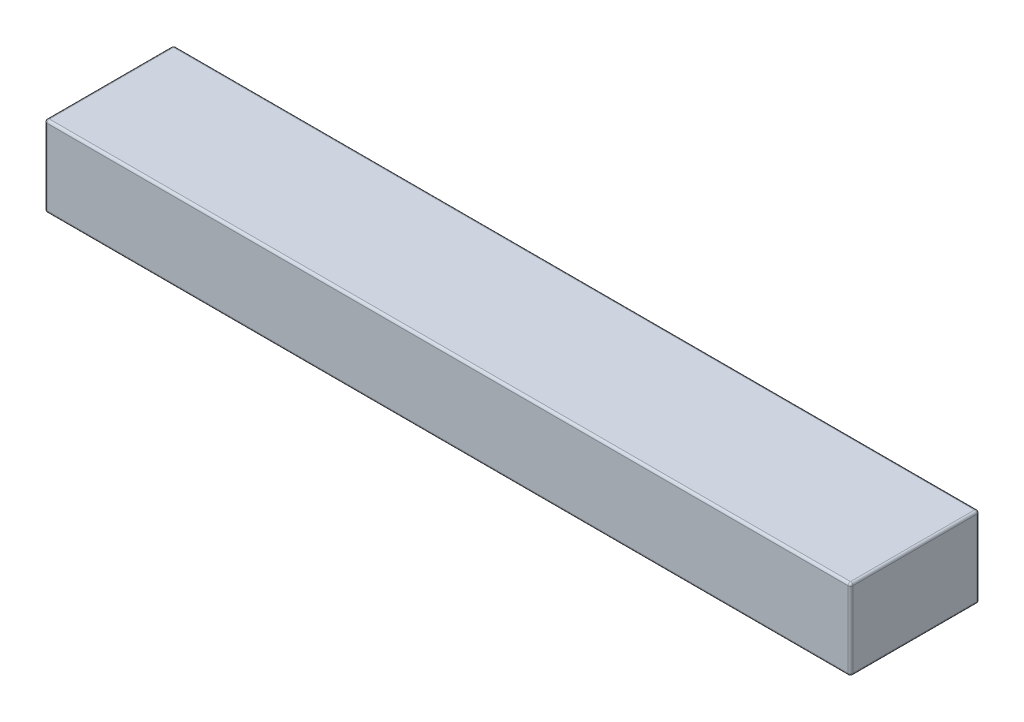
SolidWorks part; units mm, degrees
ref_plane "Front Plane" through (0, 0, 0) normal (0, 0, 1) x (1, 0, 0)
ref_plane "Top Plane" through (0, 0, 0) normal (0, 1, 0) x (1, 0, 0)
ref_plane "Right Plane" through (0, 0, 0) normal (1, 0, 0) x (0, 0, -1)
sketch "Sketch1" plane through (0, 0, 0) normal (1, 0, 0) x (0, 0, -1)
  line L1 (-7.7, -5.7) -> (7.7, -5.7)
  line L2 (-8, -5.4) -> (-8, 4)
  line L3 (-7.7, 4.3) -> (7.7, 4.3)
  line L4 (8, -5.4) -> (8, 4)
  line L5 (-8, -5.7) -> (8, 4.3) construction
  line L6 (-8, 4.3) -> (8, -5.7) construction
  arc A0 (-7.7, -5.7) -> (-8, -5.4) centre (-7.7, -5.4) cw
  arc A1 (7.7, -5.7) -> (8, -5.4) centre (7.7, -5.4) ccw
  arc A2 (7.7, 4.3) -> (8, 4) centre (7.7, 4) cw
  arc A3 (-8, 4) -> (-7.7, 4.3) centre (-7.7, 4) cw
  point P0 (0, -0.7)
  dimension "D4" = 0.3
  dimension "D1" = 10
  dimension "D2" = 16
  dimension "D3" = 4.3
extrude "Boss-Extrude1" add sketch "Sketch1" along normal mid plane 100
fillet "Fillet1" radius 0.3 16 edges at (-50, -5.7, 0) (-50, -5.6121, -7.9121) (-50, -0.7, -8) (-50, 4.2121, -7.9121) (-50, 4.3, 0) (-50, 4.2121, 7.9121) (-50, -0.7, 8) (-50, -5.6121, 7.9121) (50, -0.7, 8) (50, 4.2121, 7.9121) (50, 4.3, 0) (50, 4.2121, -7.9121) (50, -0.7, -8) (50, -5.6121, -7.9121) (50, -5.7, 0) (50, -5.6121, 7.9121)
